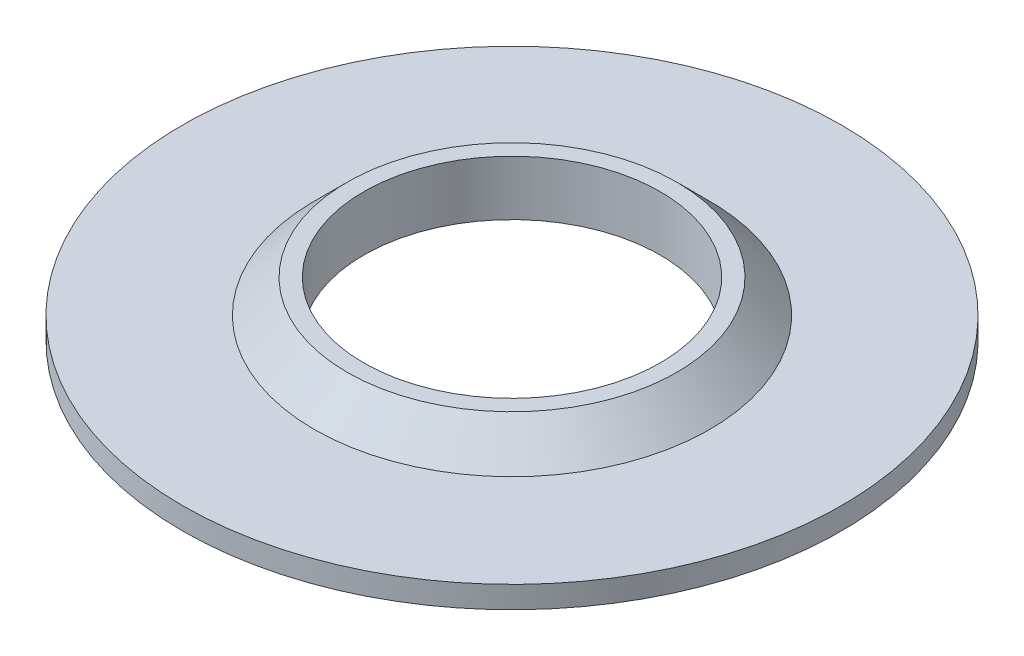
SolidWorks part; units mm, degrees
ref_plane "Спереди" through (0, 0, 0) normal (0, 0, 1) x (1, 0, 0)
ref_plane "Сверху" through (0, 0, 0) normal (0, 1, 0) x (1, 0, 0)
ref_plane "Справа" through (0, 0, 0) normal (1, 0, 0) x (0, 0, -1)
ref_axis "Ось1" through (0, 17.0134, 0) along (0, -1, 0)
sketch "Эскиз3" plane through (0, 0, 0) normal (1, 0, 0) x (0, 0, -1)
  line L0 (0, 17.0134) -> (0, -0.8102) construction
  line L1 (13.5, 0) -> (30, 0)
  line L2 (30, 0) -> (30, 2)
  line L3 (30, 2) -> (18, 2)
  line L4 (18, 2) -> (15, 5)
  line L5 (15, 5) -> (13.5, 5)
  line L7 (13.5, 5) -> (13.5, 0)
  dimension "D1" = 13.5
  dimension "D2" = 30
  dimension "D3" = 2
  dimension "D4" = 5
  dimension "D5" = 135
  dimension "D6" = 15
revolve "Повернуть1" add sketch "Эскиз3" angle 360 about axis through (0, 17.0134, 0) along (0, -1, 0)
